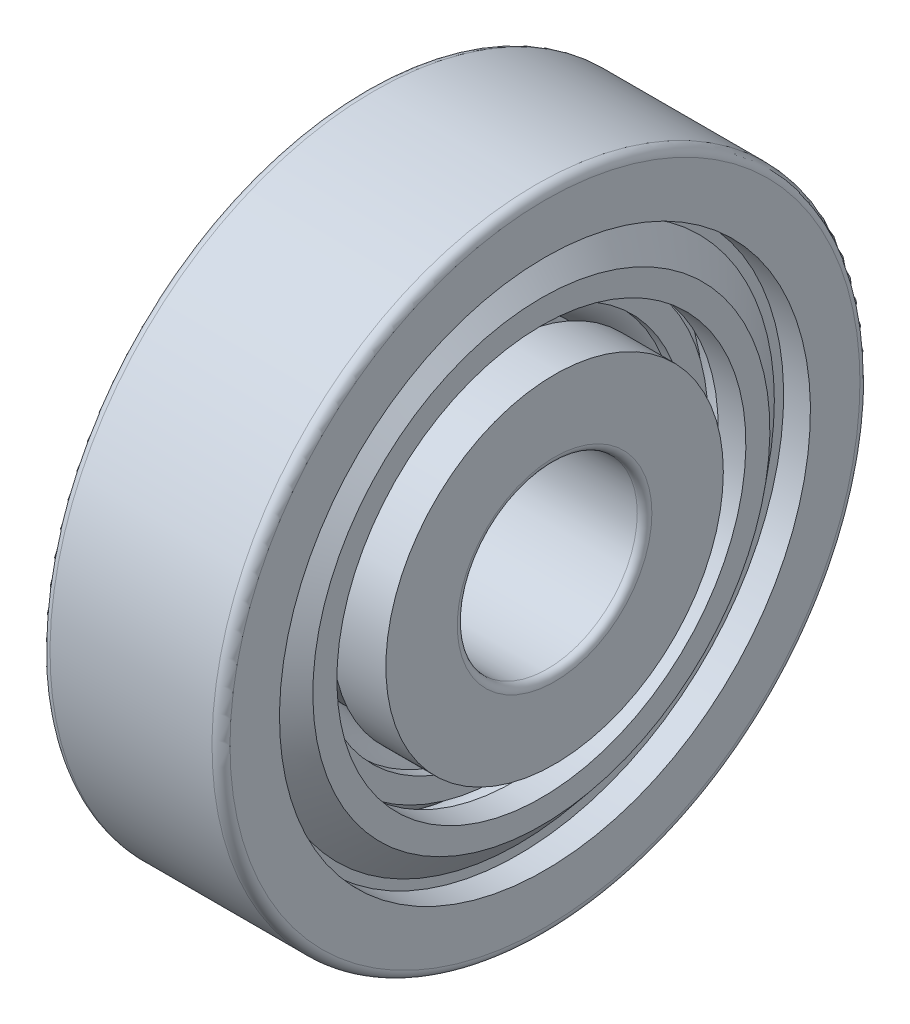
SolidWorks part; units mm, degrees
ref_plane "Front Plane" through (0, 0, 0) normal (0, 0, 1) x (1, 0, 0)
ref_plane "Top Plane" through (0, 0, 0) normal (0, 1, 0) x (1, 0, 0)
ref_plane "Right Plane" through (0, 0, 0) normal (1, 0, 0) x (0, 0, -1)
sketch "Sketch3" plane through (0, 0, 0) normal (0, 0, 1) x (1, 0, 0)
  line L0 (-3.1052, 14.0494) -> (-1.7006, 14.0494)
  line L1 (1.7006, 14.0494) -> (3.1052, 14.0494)
  line L2 (3.1052, 14.0494) -> (3.1052, 10.8228)
  line L3 (3.1052, 10.8228) -> (4.572, 10.8228)
  line L4 (4.572, 10.8228) -> (4.572, 12.0934)
  line L5 (4.572, 12.0934) -> (3.3434, 13.5576)
  line L6 (3.3434, 13.5576) -> (3.3434, 14.0494)
  line L7 (3.3434, 14.0494) -> (4.7625, 14.0494)
  line L8 (4.7625, 14.0494) -> (4.7625, 16.6687)
  line L9 (4.2862, 17.145) -> (-4.2862, 17.145)
  line L10 (-4.7625, 16.6687) -> (-4.7625, 14.0494)
  line L11 (-4.7625, 14.0494) -> (-3.3434, 14.0494)
  line L12 (-3.3434, 14.0494) -> (-3.3434, 13.5576)
  line L13 (-3.3434, 13.5576) -> (-4.572, 12.0934)
  line L14 (-4.572, 12.0934) -> (-4.572, 10.8228)
  line L15 (-4.572, 10.8228) -> (-3.1052, 10.8228)
  line L16 (-3.1052, 10.8228) -> (-3.1052, 14.0494)
  line L17 (-4.7625, 0) -> (4.7625, 0) construction
  arc A0 (-1.7006, 14.0494) -> (1.7006, 14.0494) centre (0, 12.3825) cw
  arc A1 (4.7625, 16.6687) -> (4.2862, 17.145) centre (4.2862, 16.6687) ccw
  arc A2 (-4.2862, 17.145) -> (-4.7625, 16.6687) centre (-4.2862, 16.6688) ccw
  dimension "D1" = 9.525
revolve "Revolve2" add sketch "Sketch3" angle 360 about L17
sketch "Sketch5" plane through (0, 0, 0) normal (0, 0, 1) x (1, 0, 0)
  line L0 (5.2712, 8.9297) -> (2.4344, 8.9297)
  line L1 (-1.4171, 8.9297) -> (-4.2538, 8.9297)
  line L2 (-4.2538, 8.9297) -> (-4.2535, 5.1593)
  line L3 (-3.8567, 4.7625) -> (4.8841, 4.7625)
  line L4 (5.2715, 5.1499) -> (5.2712, 8.9297)
  line L5 (-3.9688, 0) -> (3.9688, 0) construction
  arc A0 (2.4344, 8.9297) -> (-1.4171, 8.9297) centre (0.5087, 10.3656) cw
  arc A1 (-4.2535, 5.1593) -> (-3.8567, 4.7625) centre (-3.8567, 5.1594) ccw
  arc A2 (5.2715, 5.1499) -> (4.8841, 4.7625) centre (4.8841, 5.1499) cw
  dimension "D3" = 0.3873
  dimension "D4" = 0.3969
  dimension "D1" = 4.1672
  dimension "D2" = 9.525
revolve "Revolve3" add sketch "Sketch5" angle 360 about L5
sketch "Sketch7" plane through (0, 0, 0) normal (0, 0, 1) x (1, 0, 0)
  line L0 (1.893, 9.7234) -> (2.4805, 9.7234)
  line L1 (2.4805, 9.7234) -> (2.4805, 10.9141)
  line L2 (2.4805, 10.9141) -> (1.893, 10.9141)
  line L3 (-1.893, 10.9141) -> (-2.4805, 10.9141)
  line L4 (-2.4805, 10.9141) -> (-2.4805, 9.7234)
  line L5 (-2.4805, 9.7234) -> (-1.893, 9.7234)
  line L6 (-2.4805, 0) -> (2.4805, 0) construction
  arc A0 (-1.893, 9.7234) -> (1.893, 9.7234) centre (0, 10.3187) ccw
  arc A1 (1.893, 10.9141) -> (-1.893, 10.9141) centre (0, 10.3187) ccw
  dimension "D1" = 4.9609
revolve "Revolve4" add sketch "Sketch7" angle 360 about L6
